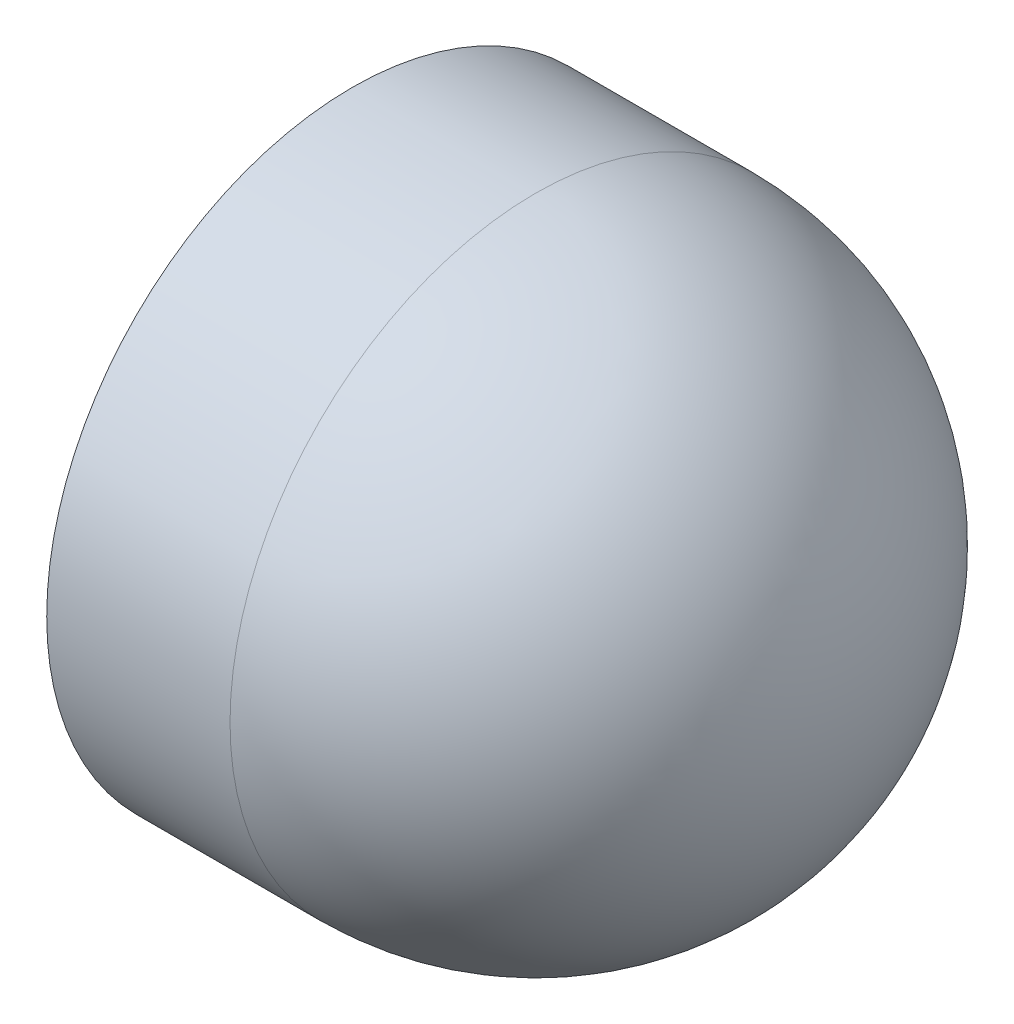
SolidWorks part; units mm, degrees
ref_plane "Front Plane" through (0, 0, 0) normal (0, 0, 1) x (1, 0, 0)
ref_plane "Top Plane" through (0, 0, 0) normal (0, 1, 0) x (1, 0, 0)
ref_plane "Right Plane" through (0, 0, 0) normal (1, 0, 0) x (0, 0, -1)
sketch "Sketch1" plane through (0, 0, 0) normal (0, 0, 1) x (1, 0, 0)
  line L0 (0, 0) -> (12, 0)
  line L1 (0, 0) -> (0, -7.5)
  line L2 (0, -7.5) -> (4.5, -7.5)
  arc A0 (4.5, -7.5) -> (12, 0) centre (4.5, 0) ccw
  dimension "D1" = 7.5
  dimension "D2" = 12
revolve "Revolve1" add sketch "Sketch1" angle 360 about L0
sketch "Sketch2" plane through (0, 0, 0) normal (-1, 0, 0) x (0, 0, 1)
  line L0 (2.0507, 3.552) -> (-2.0507, 3.552)
  line L1 (1.9774, -3.425) -> (3.9548, 0) construction
  line L2 (3.9548, 0) -> (1.9774, 3.425) construction
  line L3 (1.9774, 3.425) -> (-1.9774, 3.425) construction
  line L4 (-1.9774, 3.425) -> (-3.9548, 0) construction
  line L5 (-3.9548, 0) -> (-1.9774, -3.425) construction
  line L6 (-1.9774, -3.425) -> (1.9774, -3.425) construction
  line L7 (-2.0507, 3.552) -> (-4.1015, 0)
  line L8 (-4.1015, 0) -> (-2.0507, -3.552)
  line L9 (-2.0507, -3.552) -> (2.0507, -3.552)
  line L10 (2.0507, -3.552) -> (4.1015, 0)
  line L11 (4.1015, 0) -> (2.0507, 3.552)
  circle A0 centre (0, 0) radius 3.425 construction
  dimension "D1" = 6.85
  dimension "D2" = 0.127
extrude "Cut-Extrude1" cut sketch "Sketch2" against normal blind 2.75
sketch "Sketch3" plane through (0, 0, 0) normal (-1, 0, 0) x (0, 0, 1)
  line L0 (0, 0) -> (-4.7631, -2.75) construction
  line L1 (0, 0) -> (4.7631, -2.75) construction
  circle A0 centre (0, 5.5) radius 1 construction
  circle A1 centre (0, 0) radius 5.5 construction
  circle A2 centre (-4.7631, -2.75) radius 1 construction
  circle A3 centre (4.7631, -2.75) radius 1 construction
  circle A4 centre (-4.7631, -2.75) radius 1.127
  circle A5 centre (0, 5.5) radius 1.127
  circle A6 centre (4.7631, -2.75) radius 1.127
  dimension "D1" = 2
  dimension "D2" = 11
  dimension "D3" = 120
  dimension "D4" = 0.127
extrude "Cut-Extrude2" cut sketch "Sketch3" against normal blind 2.1
ref_plane "Plane1" through (12, 0, 0) normal (1, 0, 0) x (0, 0, -1)
